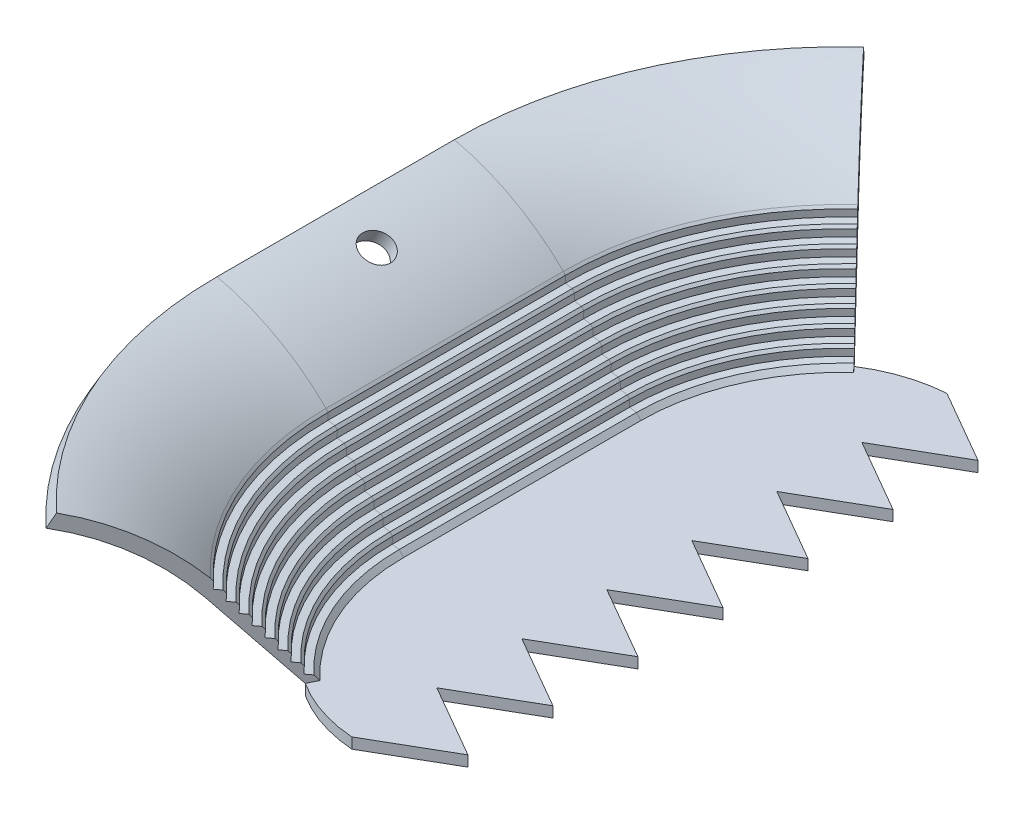
SolidWorks part; units mm, degrees
ref_plane "Front Plane" through (0, 0, 0) normal (0, 0, 1) x (1, 0, 0)
ref_plane "Top Plane" through (0, 0, 0) normal (0, 1, 0) x (1, 0, 0)
ref_plane "Right Plane" through (0, 0, 0) normal (1, 0, 0) x (0, 0, -1)
sketch "Sketch1" plane through (0, 0, 0) normal (0, 0, 1) x (1, 0, 0)
  line L0 (0, 0) -> (-56.2176, 0) construction
  line L8 (-5.6359, 7.157) -> (1, 0)
  line L9 (-16.2506, 13.11) -> (-15.5645, 14.332)
  line L11 (-5.3062, 8.737) -> (1.978, 0.2084)
  line L12 (1.978, 0.2084) -> (1, 0)
  line L13 (-16.2506, 13.11) -> (2.1364, 13.11) construction
  arc A1 (-16.2506, 13.11) -> (-5.6359, 7.157) centre (-20.2626, -6.4835) cw
  arc A2 (-15.5645, 14.332) -> (-5.3062, 8.737) centre (-20.2626, -6.4835) cw
  dimension "D2" = 1
  dimension "D4" = 20
  dimension "D5" = 60.69
  dimension "D7" = 21.339
  dimension "D3" = 192.03
  dimension "D6" = 47.163
  dimension "D8" = 1
  dimension "D9" = 9.76
  dimension "D10" = 13.11
  dimension "D11" = 12.17
  dimension "D12" = 1.58
extrude "Boss-Extrude1" add sketch "Sketch1" along normal mid plane 13.33
sketch "Sketch2" plane through (0, 0, 6.665) normal (0, 0, 1) x (1, 0, 0)
  line L0 (-5.1114, 8.5088) -> (-5.1312, 7.8391)
  line L1 (-5.1312, 7.8391) -> (-4.4666, 7.7539)
  line L3 (1.978, 0.2084) -> (-5.3062, 8.737) construction
  line L4 (-4.789, 8.1314) -> (-5.5469, 7.4841) construction
  dimension "D1" = 0.67
  dimension "D2" = 0.45
  dimension "D3" = 0.3
extrude "Cut-Extrude2" cut sketch "Sketch2" against normal through all and the other way through all
pattern_linear "LPattern1" count 8 spacing 1.33 along (0.6495, -0.7604, 0) of "Cut-Extrude2"
sketch "Sketch3" plane through (0, 0, 6.665) normal (0, 0, 1) x (1, 0, 0)
  line L48 (-5.1114, 8.5088) -> (-5.3062, 8.737) construction
  line L49 (-5.1114, 8.5088) -> (-5.1312, 7.8391) construction
  line L50 (-5.1312, 7.8391) -> (-4.4666, 7.7539) construction
  line L51 (-4.2476, 7.4975) -> (-4.4666, 7.7539) construction
  line L52 (-4.2476, 7.4975) -> (-4.2674, 6.8278) construction
  line L53 (-4.2674, 6.8278) -> (-3.6028, 6.7426) construction
  line L54 (-3.3838, 6.4862) -> (-3.6028, 6.7426) construction
  line L55 (-3.3838, 6.4862) -> (-3.4036, 5.8165) construction
  line L56 (-3.4036, 5.8165) -> (-2.739, 5.7313) construction
  line L57 (-2.52, 5.4749) -> (-2.739, 5.7313) construction
  line L58 (-2.52, 5.4749) -> (-2.5398, 4.8051) construction
  line L59 (-2.5398, 4.8051) -> (-1.8753, 4.7199) construction
  line L60 (-1.6563, 4.4635) -> (-1.8753, 4.7199) construction
  line L61 (-1.6563, 4.4635) -> (-1.676, 3.7938) construction
  line L62 (-1.676, 3.7938) -> (-1.0115, 3.7086) construction
  line L63 (-0.7925, 3.4522) -> (-1.0115, 3.7086) construction
  line L64 (-0.7925, 3.4522) -> (-0.8123, 2.7825) construction
  line L65 (-0.8123, 2.7825) -> (-0.1477, 2.6973) construction
  line L66 (0.0713, 2.4409) -> (-0.1477, 2.6973) construction
  line L67 (0.0713, 2.4409) -> (0.0515, 1.7712) construction
  line L68 (0.0515, 1.7712) -> (0.7161, 1.686) construction
  line L69 (0.9351, 1.4295) -> (0.7161, 1.686) construction
  line L70 (0.9351, 1.4295) -> (0.9153, 0.7598) construction
  line L71 (0.9153, 0.7598) -> (1.5798, 0.6746) construction
  line L72 (1.978, 0.2084) -> (1.5798, 0.6746) construction
  line L73 (1, 0) -> (1.978, 0.2084) construction
  line L74 (-5.6359, 7.157) -> (1, 0) construction
  line L75 (-15.5645, 14.332) -> (-16.2506, 13.11) construction
  line L76 (-5.1114, 8.5088) -> (-5.3062, 8.737)
  line L77 (-5.1114, 8.5088) -> (-5.1312, 7.8391)
  line L78 (-5.1312, 7.8391) -> (-4.4666, 7.7539)
  line L79 (-4.2476, 7.4975) -> (-4.4666, 7.7539)
  line L80 (-4.2476, 7.4975) -> (-4.2674, 6.8278)
  line L81 (-4.2674, 6.8278) -> (-3.6028, 6.7426)
  line L82 (-3.3838, 6.4862) -> (-3.6028, 6.7426)
  line L83 (-3.3838, 6.4862) -> (-3.4036, 5.8165)
  line L84 (-3.4036, 5.8165) -> (-2.739, 5.7313)
  line L85 (-2.52, 5.4749) -> (-2.739, 5.7313)
  line L86 (-2.52, 5.4749) -> (-2.5398, 4.8051)
  line L87 (-2.5398, 4.8051) -> (-1.8753, 4.7199)
  line L88 (-1.6563, 4.4635) -> (-1.8753, 4.7199)
  line L89 (-1.6563, 4.4635) -> (-1.676, 3.7938)
  line L90 (-1.676, 3.7938) -> (-1.0115, 3.7086)
  line L91 (-0.7925, 3.4522) -> (-1.0115, 3.7086)
  line L92 (-0.7925, 3.4522) -> (-0.8123, 2.7825)
  line L93 (-0.8123, 2.7825) -> (-0.1477, 2.6973)
  line L94 (0.0713, 2.4409) -> (-0.1477, 2.6973)
  line L95 (0.0713, 2.4409) -> (0.0515, 1.7712)
  line L96 (0.0515, 1.7712) -> (0.7161, 1.686)
  line L97 (0.9351, 1.4295) -> (0.7161, 1.686)
  line L98 (0.9351, 1.4295) -> (0.9153, 0.7598)
  line L99 (0.9153, 0.7598) -> (1.5798, 0.6746)
  line L100 (1.978, 0.2084) -> (1.5798, 0.6746)
  line L101 (1, 0) -> (1.978, 0.2084)
  line L102 (-5.6359, 7.157) -> (1, 0)
  line L103 (-15.5645, 14.332) -> (-16.2506, 13.11)
  arc A4 (-5.6359, 7.157) -> (-16.2506, 13.11) centre (-20.2626, -6.4835) ccw construction
  arc A5 (-5.3062, 8.737) -> (-15.5645, 14.332) centre (-20.2626, -6.4835) ccw construction
  arc A6 (-5.6359, 7.157) -> (-16.2506, 13.11) centre (-20.2626, -6.4835) ccw
  arc A7 (-5.3062, 8.737) -> (-15.5645, 14.332) centre (-20.2626, -6.4835) ccw
sketch "Sketch5" plane through (0, 0, 0) normal (0, 1, 0) x (1, 0, 0)
  line L0 (1, -6.665) -> (1, -11.165)
  arc A0 (1, -11.165) -> (7.4, -25.8292) centre (21, -11.165) ccw
  dimension "D3" = 20
  dimension "D1" = 4.5
  dimension "D2" = 16
sweep "Sweep1" add profiles "Sketch3" path "Sketch5"
mirror "Mirror1" about plane through (0, 0, 0) normal (0, 0, 1) of "Sweep1"
sketch "Sketch9" plane through (0, 0, 0) normal (0, 1, 0) x (1, 0, 0)
  line L0 (13.9496, 20) -> (20.8778, 24)
  line L1 (20.8778, 24) -> (13.9496, 28)
  line L2 (1, -11.165) -> (1, 11.165) construction
  line L5 (1, -11.165) -> (1, 11.165)
  line L11 (13.9496, 0) -> (0, 0) construction
  line L20 (13.9496, 20) -> (20.8778, 16)
  line L21 (20.8778, 16) -> (13.9496, 12)
  line L22 (13.9496, 12) -> (20.8778, 8)
  line L23 (20.8778, 8) -> (13.9496, 4)
  line L24 (13.9496, 4) -> (20.8778, 0)
  line L25 (20.8778, 0) -> (13.9496, -4)
  line L26 (13.9496, -4) -> (20.8778, -8)
  line L27 (20.8778, -8) -> (13.9496, -12)
  line L28 (13.9496, -12) -> (20.8778, -16)
  line L29 (20.8778, -16) -> (13.9496, -20)
  line L30 (13.9496, -20) -> (20.8778, -24)
  line L31 (20.8778, -24) -> (13.9496, -28)
  arc A0 (7.4, 25.8292) -> (1, 11.165) centre (21, 11.165) ccw construction
  arc A1 (1, -11.165) -> (7.4, -25.8292) centre (21, -11.165) ccw construction
  arc A2 (7.4, 25.8292) -> (1, 11.165) centre (21, 11.165) ccw
  arc A3 (1, -11.165) -> (7.4, -25.8292) centre (21, -11.165) ccw
  arc A4 (7.4, 25.8292) -> (13.9496, 28) centre (14.9434, 14.0353) cw
  arc A5 (7.4, -25.8292) -> (13.9496, -28) centre (14.9434, -14.0353) ccw
  dimension "D5" = 14
  dimension "D1" = 28
  dimension "D2" = 8
  dimension "D3" = 28
  dimension "D4" = 6.9
  dimension "D6" = 8
  dimension "D7" = 8
  dimension "D8" = 8
  dimension "D9" = 8
  dimension "D10" = 8
  dimension "D11" = 8
  dimension "D12" = 8
extrude "Boss-Extrude2" add sketch "Sketch9" against normal blind 1 separate body
ref_plane "Plane1" through (2.3235, 10.2946, 0) normal (0.2202, 0.9755, 0) x (0.9755, -0.2202, 0)
sketch "Sketch11" plane through (2.3235, 10.2946, 0) normal (0.2202, 0.9755, 0) x (0.9755, -0.2202, 0)
  line L0 (-18.338, -11.165) -> (-18.338, 11.165) construction
  circle A0 centre (-14.338, 0.005) radius 1.425
  dimension "D2" = 2.85
  dimension "D1" = 4
  dimension "D3" = 11.17
extrude "Cut-Extrude3" [suppressed] cut sketch "Sketch11" against normal blind 10
extrude "Cut-Extrude4" cut sketch "Sketch12" against normal through all
sketch "Sketch12" plane through (-25.0923, 18.0673, 6.665) normal (-0.489, -0.8723, 0) x (-0.8723, 0.489, 0)
  circle A1 centre (-14.1366, 6.665) radius 1.425
